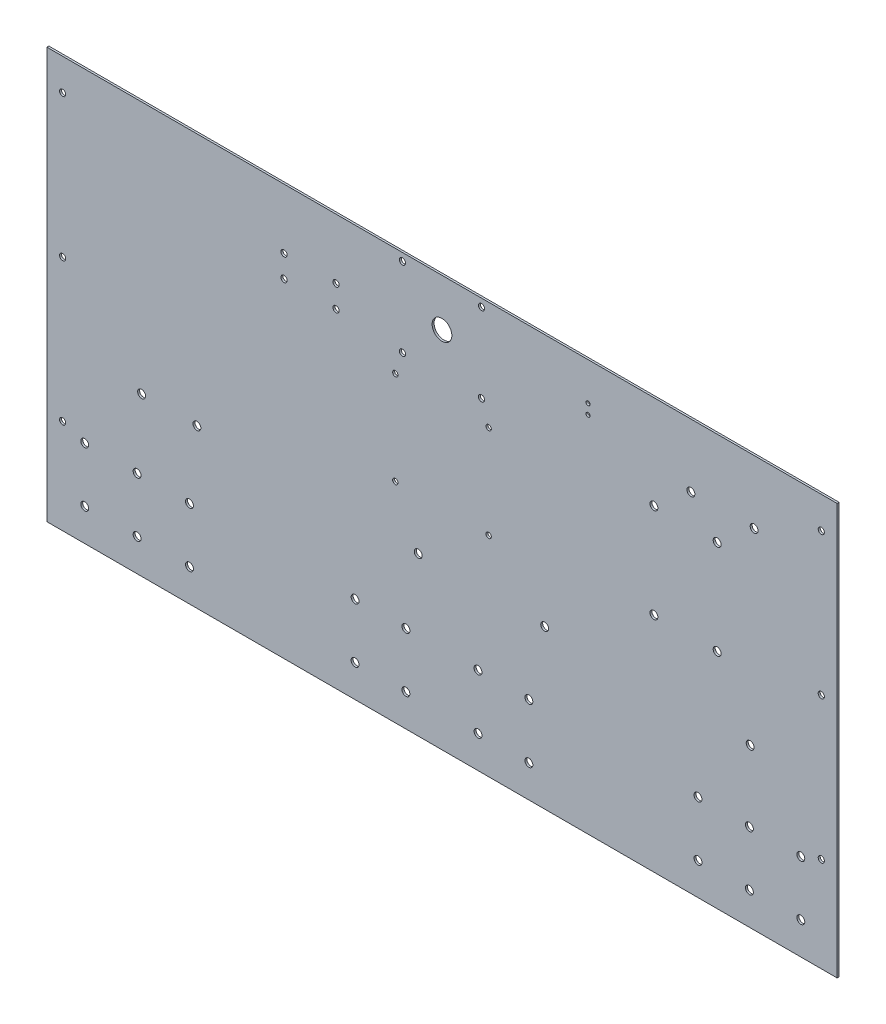
SolidWorks part; units mm, degrees
material "ABS PC"
ref_plane "Front Plane" through (0, 0, 0) normal (0, 0, 1) x (1, 0, 0)
ref_plane "Top Plane" through (0, 0, 0) normal (0, 1, 0) x (1, 0, 0)
ref_plane "Right Plane" through (0, 0, 0) normal (1, 0, 0) x (0, 0, -1)
sketch "Sketch1" plane through (0, 0, 0) normal (0, 0, 1) x (1, 0, 0)
  line L1 (-317.5, -165.1) -> (317.5, -165.1)
  line L2 (-317.5, -165.1) -> (-317.5, 165.1)
  line L3 (-317.5, 165.1) -> (317.5, 165.1)
  line L4 (317.5, -165.1) -> (317.5, 165.1)
  line L5 (0, 165.1) -> (0, -165.1) construction
  line L6 (-317.5, 0) -> (317.5, 0) construction
  point P0 (0, 0)
  point P4 (-222.25, 0)
  point P5 (222.25, 0)
  point P6 (0, 115.57)
  point P7 (0, -115.57)
  dimension "Length" = 635
  dimension "Width" = 330.2
  dimension "Break" = 95.25
  dimension "D2" = 95.25
  dimension "D1" = 49.53
  dimension "D3" = 49.53
sketch "Sketch2" plane through (0, 0, 0) normal (1, 0, 0) x (0, 0, -1)
  line L0 (-0.7937, -165.1) -> (0.7937, -165.1)
  dimension "Thickness" = 1.5875
sketch "Sketch3" plane through (0, 0, 0) normal (0, 0, 1) x (1, 0, 0)
  line L0 (-317.5, -165.1) -> (-317.5, 165.1) construction
  line L1 (-317.5, -165.1) -> (317.5, -165.1) construction
  line L2 (317.5, -165.1) -> (317.5, 165.1) construction
  line L3 (-317.5, 165.1) -> (317.5, 165.1) construction
  line L4 (-317.5, -165.1) -> (-317.5, 165.1)
  line L5 (-317.5, -165.1) -> (317.5, -165.1)
  line L6 (317.5, -165.1) -> (317.5, 165.1)
  line L7 (-317.5, 165.1) -> (317.5, 165.1)
extrude "Boss-Extrude1" add sketch "Sketch3" along normal mid plane 1.5875
sketch "Sketch4" plane through (0, 0, 0.7937) normal (0, 0, 1) x (1, 0, 0)
  line L0 (-317.5, 165.1) -> (-304.8, 165.1) construction
  line L1 (317.5, 165.1) -> (-317.5, 165.1) construction
  line L2 (-304.8, 165.1) -> (-304.8, 139.7) construction
  line L3 (-304.8, 139.7) -> (-304.8, 25.4) construction
  line L4 (-304.8, 25.4) -> (-304.8, -88.9) construction
  line L5 (317.5, 165.1) -> (304.8, 165.1) construction
  line L6 (304.8, 165.1) -> (304.8, 139.7) construction
  line L7 (304.8, 139.7) -> (304.8, 25.4) construction
  line L8 (304.8, 25.4) -> (304.8, -88.9) construction
  dimension "D1" = 25.4
  dimension "D2" = 114.3
  dimension "D3" = 114.3
hole_wizard "#10 Clearance Hole1" positions "Sketch5" profile "Sketch6" hole size "#10" standard "ANSI Inch" end condition through all
sketch "Sketch5" plane through (0, 0, 0.7937) normal (0, 0, 1) x (1, 0, 0)
  point P0 (-304.8, 139.7)
  point P4 (-304.8, 25.4)
  point P7 (-304.8, -88.9)
  point P10 (304.7359, 139.7)
  point P12 (304.7359, 25.4)
  point P14 (304.7359, -88.9)
sketch "Sketch6" plane through (-304.8, 139.7, 0.7937) normal (1, 0, 0) x (0, -1, 0)
  line L0 (0, 0) -> (0, 1.5875)
  line L1 (0, 1.5875) -> (2.4892, 1.5875)
  line L2 (2.4892, 1.5875) -> (2.4892, 0)
  line L5 (2.4892, 0) -> (0, 0)
  line L11 (0, -6.35) -> (0, 107.95) construction
  dimension "Thru Hole Dia." = 4.9784
  dimension "Thru Hole Depth" = 1.5875
sketch "Sketch7" plane through (0, 0, -0.7937) normal (0, 0, -1) x (-1, 0, 0)
  line L0 (-117.2884, 134.7) -> (-117.2884, 165.1) construction
  line L1 (-317.5, 165.1) -> (317.5, 165.1) construction
  line L2 (-117.2884, 134.7) -> (-292.0404, 134.7) construction
  line L3 (-292.0404, -276.662) -> (-292.0404, 333.2902) construction
  line L4 (-117.2884, 134.7) -> (-117.2884, 126.7) construction
  dimension "D1" = 30.4
  dimension "D2" = 174.752
hole_wizard "Ø3.2 (3.2) Diameter Hole1" positions "Sketch8" profile "Sketch9" hole size "Ø3.2" standard "ANSI Metric" end condition through all
sketch "Sketch8" plane through (0, 0, 0.7937) normal (0, 0, 1) x (1, 0, 0)
  point P0 (117.2884, 134.7)
  point P3 (117.2884, 126.7)
sketch "Sketch9" plane through (117.2884, 134.7, 0.7937) normal (1, 0, 0) x (0, -1, 0)
  line L0 (0, 0) -> (0, 1.5875)
  line L1 (0, 1.5875) -> (1.6, 1.5875)
  line L2 (1.6, 1.5875) -> (1.6, 0)
  line L5 (1.6, 0) -> (0, 0)
  line L11 (0, -6.35) -> (0, 107.95) construction
  dimension "Thru Hole Dia." = 3.2
  dimension "Thru Hole Depth" = 1.5875
sketch "Sketch10" plane through (0, 0, -0.7937) normal (0, 0, -1) x (-1, 0, 0)
  line L0 (-284.4283, -92.2986) -> (-284.4283, -98.0365) construction
  line L1 (-284.4283, -95.1676) -> (-292.0404, -95.1676) construction
  line L2 (-292.0404, -276.662) -> (-292.0404, 333.2902) construction
  line L3 (-292.0404, -95.1676) -> (292.1, -95.1676) construction
  line L4 (292.1, -276.662) -> (292.1, 333.2902) construction
  line L5 (239.9592, -95.1676) -> (250.0109, -95.1676) construction
  line L6 (239.9592, -98.1417) -> (239.9592, -92.6748) construction
  line L7 (250.0109, -98.0969) -> (250.0109, -92.6301) construction
  line L8 (-284.4283, -142.0365) -> (-284.4283, -136.2986) construction
  line L9 (-284.4283, -139.1676) -> (-292.0404, -139.1676) construction
  line L10 (-292.0404, -139.1676) -> (292.1, -139.1676) construction
  line L11 (239.878, -142.2772) -> (239.878, -136.5393) construction
  line L12 (250.0921, -142.2324) -> (250.0921, -136.4945) construction
  line L13 (239.878, -139.1676) -> (250.0921, -139.1676) construction
  line L14 (-251.2911, -98.0365) -> (-251.2911, -92.2986) construction
  line L15 (-242.6447, -92.1105) -> (-242.6447, -97.8484) construction
  line L16 (-251.2911, -95.1676) -> (-242.6447, -95.1676) construction
  line L17 (-251.2099, -139.1676) -> (-242.7258, -139.1676) construction
  line L18 (-251.2099, -136.4342) -> (-251.2099, -141.901) construction
  line L19 (-242.7258, -136.246) -> (-242.7258, -141.7129) construction
  line L20 (-285.1097, -95.1676) -> (-288.2847, -95.1676) construction
  line L21 (-285.1097, -84.5426) -> (-285.1097, -149.7926) construction
  line L22 (-285.1097, -139.1676) -> (-288.2847, -139.1676) construction
  line L23 (-208.8261, -95.1676) -> (-205.6511, -95.1676) construction
  line L24 (-208.8261, -149.6044) -> (-208.8261, -84.3544) construction
  line L25 (-208.8261, -139.1676) -> (-205.6511, -139.1676) construction
  line L26 (-66.6154, -95.1676) -> (-69.7904, -95.1676) construction
  line L27 (-66.6154, -85.5097) -> (-66.6154, -150.7597) construction
  line L28 (-69.7904, -95.1676) -> (-69.7904, -139.1676) construction
  line L29 (32.175, -95.1676) -> (29, -95.1676) construction
  line L30 (32.175, -83.9052) -> (32.175, -149.1552) construction
  line L31 (29, -95.1676) -> (29, -139.1676) construction
  line L32 (-32.1154, -95.1676) -> (-28.9404, -95.1676) construction
  line L33 (-32.1154, -150.7597) -> (-32.1154, -85.5097) construction
  line L34 (-28.9404, -95.1676) -> (-28.9404, -139.1676) construction
  line L35 (66.675, -95.1676) -> (69.85, -95.1676) construction
  line L36 (66.675, -149.1552) -> (66.675, -83.9052) construction
  line L37 (69.85, -95.1676) -> (69.85, -139.1676) construction
  line L38 (206.0594, -95.1676) -> (202.8844, -95.1676) construction
  line L39 (206.0594, -84.7833) -> (206.0594, -150.0333) construction
  line L40 (202.8844, -95.1676) -> (202.8844, -139.1676) construction
  line L41 (283.9107, -95.1676) -> (287.0857, -95.1676) construction
  line L42 (287.0857, -95.1676) -> (287.0857, -139.1676) construction
  point P90 (-246.9679, -95.1676)
  point P91 (-246.9679, -139.1676)
  point P92 (244.985, -95.1676)
  point P93 (244.985, -139.1676)
hole_wizard "1/4 (0.25) Diameter Hole1" positions "Sketch11" profile "Sketch12" hole size "1/4" standard "ANSI Inch" end condition through all
sketch "Sketch11" plane through (0, 0, 0.7937) normal (0, 0, 1) x (1, 0, 0)
  point P0 (-287.0857, -95.1676)
  point P3 (-287.0857, -139.1676)
  point P6 (-202.8844, -95.1676)
  point P9 (-202.8844, -139.1676)
  point P12 (-69.85, -95.1676)
  point P15 (-69.85, -139.1676)
  point P18 (-29, -139.1676)
  point P21 (-29, -95.1676)
  point P24 (28.9404, -95.1676)
  point P27 (28.9404, -139.1676)
  point P30 (69.7904, -139.1676)
  point P33 (69.7904, -95.1676)
  point P36 (205.6511, -95.1676)
  point P39 (205.6511, -139.1676)
  point P42 (288.2847, -95.1676)
  point P45 (288.2847, -139.1676)
  point P49 (-244.985, -95.1676)
  point P52 (-244.985, -139.1676)
  point P55 (246.9679, -95.1676)
  point P58 (246.9679, -139.1676)
sketch "Sketch12" plane through (-287.0857, -95.1676, 0.7937) normal (1, 0, 0) x (0, -1, 0)
  line L0 (0, 0) -> (0, 1.5875)
  line L1 (0, 1.5875) -> (3.175, 1.5875)
  line L2 (3.175, 1.5875) -> (3.175, 0)
  line L5 (3.175, 0) -> (0, 0)
  line L11 (0, -6.35) -> (0, 107.95) construction
  dimension "Thru Hole Dia." = 6.35
  dimension "Thru Hole Depth" = 1.5875
hole_wizard "#10 Clearance Hole2" positions "Sketch18" profile "Sketch19" hole size "#10" standard "ANSI Inch" end condition through all
sketch "Sketch18" plane through (0, 0, -0.7937) normal (0, 0, -1) x (-1, 0, 0)
  point P0 (-31.7202, 158.8867)
  point P3 (-31.7202, 95.3867)
  point P6 (31.7798, 95.3867)
  point P9 (31.7798, 158.8867)
  point P12 (85.1279, 98.9314)
  point P15 (85.1279, 116.9037)
  point P18 (126.9212, 99.1237)
  point P21 (126.9212, 116.9037)
sketch "Sketch19" plane through (31.7202, 158.8867, -0.7937) normal (1, 0, 0) x (0, 1, 0)
  line L0 (0, 0) -> (0, 1.5875)
  line L1 (0, 1.5875) -> (2.4892, 1.5875)
  line L2 (2.4892, 1.5875) -> (2.4892, 0)
  line L5 (2.4892, 0) -> (0, 0)
  line L11 (0, -6.35) -> (0, 107.95) construction
  dimension "Thru Hole Dia." = 4.9784
  dimension "Thru Hole Depth" = 1.5875
sketch "Sketch20" plane through (0, 0, 0.7937) normal (0, 0, 1) x (1, 0, 0)
  circle A0 centre (-0.0298, 127.1367) radius 7.9375
extrude "Cut-Extrude1" cut sketch "Sketch20" against normal through all
hole_wizard "#8 Clearance Hole1" positions "Sketch21" profile "Sketch22" hole size "#8" standard "ANSI Inch" end condition through all
sketch "Sketch21" plane through (0, 0, -0.7937) normal (0, 0, -1) x (-1, 0, 0)
  point P0 (37.5298, 77.8886)
  point P3 (-37.4702, 77.8886)
  point P6 (-37.4702, 2.8886)
  point P9 (37.5298, 2.8886)
sketch "Sketch22" plane through (-37.5298, 77.8886, -0.7937) normal (1, 0, 0) x (0, 1, 0)
  line L0 (0, 0) -> (0, 1.5875)
  line L1 (0, 1.5875) -> (2.1526, 1.5875)
  line L2 (2.1526, 1.5875) -> (2.1526, 0)
  line L5 (2.1526, 0) -> (0, 0)
  line L11 (0, -6.35) -> (0, 107.95) construction
  dimension "Thru Hole Dia." = 4.3053
  dimension "Thru Hole Depth" = 1.5875
sketch "Sketch23" plane through (0, 0, -0.7937) normal (0, 0, -1) x (-1, 0, 0)
  line L0 (-195.6513, 86.6016) -> (-170.2513, 86.6016) construction
  line L1 (-160.1513, 86.6016) -> (-231.1513, 86.6016) construction
  line L2 (-170.2513, 86.6016) -> (-170.2513, 89.7766) construction
  line L3 (-170.2513, 89.7766) -> (-221.0513, 89.7766) construction
  line L4 (-195.6513, 17.1016) -> (-170.2513, 17.1016) construction
  line L5 (-231.1513, 17.1016) -> (-160.1513, 17.1016) construction
  line L6 (-170.2513, 17.1016) -> (-170.2513, 13.9266) construction
  line L7 (-170.2513, 13.9266) -> (-221.0513, 13.9266) construction
  line L8 (-292.0404, 165.1) -> (-292.0404, 114.3) construction
  line L9 (-292.0404, -276.662) -> (-292.0404, 333.2902) construction
  line L10 (-317.5, 165.1) -> (317.5, 165.1) construction
  line L11 (-292.0404, 114.3) -> (-250.7654, 114.3) construction
  line L12 (-250.7654, 114.3) -> (-199.9654, 114.3) construction
  line L13 (-292.0404, -165.1) -> (-292.0404, -38.1) construction
  line L14 (317.5, -165.1) -> (-317.5, -165.1) construction
  line L15 (-292.0404, -38.1) -> (-247.5904, -38.1) construction
  line L16 (-247.5904, -38.1) -> (-82.4904, -38.1) construction
  line L17 (-82.4904, -38.1) -> (19.1096, -38.1) construction
  line L18 (19.1096, -38.1) -> (196.9096, -38.1) construction
  line L19 (196.9096, -38.1) -> (241.3596, -38.1) construction
  dimension "D1" = 50.8
  dimension "D2" = 41.275
  dimension "D3" = 50.8
  dimension "D4" = 44.45
  dimension "D5" = 165.1
  dimension "D6" = 101.6
  dimension "D7" = 177.8
  dimension "D8" = 44.45
hole_wizard "1/4 (0.25) Diameter Hole2" positions "Sketch24" profile "Sketch25" hole size "1/4" standard "ANSI Inch" end condition through all
sketch "Sketch24" plane through (0, 0, -0.7937) normal (0, 0, -1) x (-1, 0, 0)
  point P0 (-221.0513, 89.7766)
  point P3 (-170.2513, 89.7766)
  point P6 (-221.0513, 13.9266)
  point P9 (-170.2513, 13.9266)
  point P13 (-250.7654, 114.3)
  point P16 (-199.9654, 114.3)
  point P20 (-247.5904, -38.1)
  point P23 (-82.4904, -38.1)
  point P26 (19.1096, -38.1)
  point P29 (196.9096, -38.1)
  point P32 (241.3596, -38.1)
sketch "Sketch25" plane through (221.0513, 89.7766, -0.7937) normal (1, 0, 0) x (0, 1, 0)
  line L0 (0, 0) -> (0, 1.5875)
  line L1 (0, 1.5875) -> (3.175, 1.5875)
  line L2 (3.175, 1.5875) -> (3.175, 0)
  line L5 (3.175, 0) -> (0, 0)
  line L11 (0, -6.35) -> (0, 107.95) construction
  dimension "Thru Hole Dia." = 6.35
  dimension "Thru Hole Depth" = 1.5875
equation "\"D1@Boss-Extrude1\"=\"thickness@sketch2\""
equation "\"Break@Sketch1\" = \"Length@Sketch1\" * 0.15"
equation "\"D2@Sketch1\" = \"Break@Sketch1\""
equation "\"D1@Sketch1\"=\"Width@Sketch1\"*0.15"
equation "\"D3@Sketch1\"=\"D1@Sketch1\""
